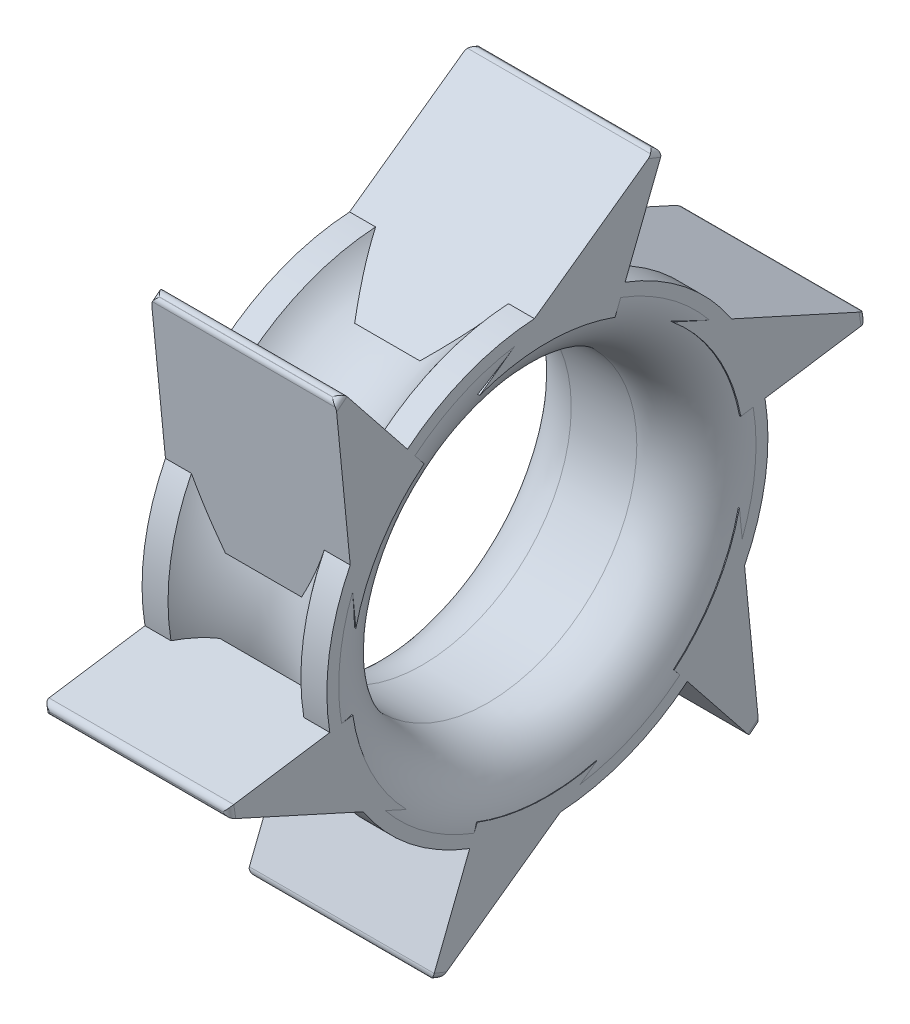
SolidWorks part; units mm, degrees
ref_plane "Front Plane" through (0, 0, 0) normal (0, 0, 1) x (1, 0, 0)
ref_plane "Top Plane" through (0, 0, 0) normal (0, 1, 0) x (1, 0, 0)
ref_plane "Right Plane" through (0, 0, 0) normal (1, 0, 0) x (0, 0, -1)
sketch "Sketch1" plane through (0, 0, 0) normal (0, 0, 1) x (1, 0, 0)
  line L0 (11.1435, 37) -> (15.5, 37)
  line L1 (-15.5, 37) -> (-11.1435, 37)
  line L2 (-15.5, 37) -> (-15.5, 25)
  line L3 (-15.5, 25) -> (15.5, 25)
  line L4 (15.5, 37) -> (15.5, 25)
  line L5 (-15.5, 37) -> (15.5, 25) construction
  line L6 (-15.5, 25) -> (15.5, 37) construction
  line L7 (0, 0) -> (-44.1868, 0) construction
  line L8 (-44.1868, 0) -> (70.9544, 0) construction
  arc A0 (-11.1435, 37) -> (11.1435, 37) centre (0, 45) ccw
  point P0 (0, 31)
  point P8 (0, 25)
  dimension "D4" = 8
  dimension "D1" = 25
  dimension "D2" = 37
  dimension "D3" = 31
revolve "Revolve1" add sketch "Sketch1" angle 360 about L8
fillet "Fillet1" radius 10 2 edges at (-15.5, 0, 25) (15.5, 0, 25)
sketch "Sketch2" plane through (0, 0, 0) normal (1, 0, 0) x (0, 0, -1)
  line L0 (0, -0.6164) -> (0, 55.3462) construction
  line L1 (-56.5594, 59.2727) -> (-53.6248, 59.2727)
  line L2 (19.3584, 50.7239) -> (11.3584, 30.3672)
  line L3 (0, -0.6164) -> (33.4372, 45.5458) construction
  line L4 (-11.3584, 30.3672) -> (17.8913, 51.298)
  line L5 (17.8913, 51.298) -> (19.3584, 50.7239)
  line L6 (20.6196, 25.0203) -> (53.371, 10.1547)
  line L7 (53.6074, 8.5971) -> (31.978, 5.3469)
  line L8 (53.371, 10.1547) -> (53.6074, 8.5971)
  line L9 (31.978, -5.3469) -> (35.4798, -41.1433)
  line L10 (34.249, -42.1268) -> (20.6196, -25.0203)
  line L11 (35.4798, -41.1433) -> (34.249, -42.1268)
  line L12 (11.3584, -30.3672) -> (-17.8913, -51.298)
  line L13 (-19.3584, -50.7239) -> (-11.3584, -30.3672)
  line L14 (-17.8913, -51.298) -> (-19.3584, -50.7239)
  line L15 (-20.6196, -25.0203) -> (-53.371, -10.1547)
  line L16 (-53.6074, -8.5971) -> (-31.978, -5.3469)
  line L17 (-53.371, -10.1547) -> (-53.6074, -8.5971)
  line L18 (-31.978, 5.3469) -> (-35.4798, 41.1433)
  line L19 (-34.249, 42.1268) -> (-20.6196, 25.0203)
  line L20 (-35.4798, 41.1433) -> (-34.249, 42.1268)
  circle A0 centre (0, -0.6164) radius 33
  circle A2 centre (0, -0.6164) radius 57 construction
  arc A4 (-15.0607, 28.7464) -> (19.3584, 26.1091) centre (0, -0.6164) cw
  circle A6 centre (0, -0.6164) radius 33
  circle A8 centre (0, -0.6164) radius 33
  circle A10 centre (0, -0.6164) radius 33
  circle A12 centre (0, -0.6164) radius 33
  circle A14 centre (0, -0.6164) radius 33
  circle A16 centre (0, -0.6164) radius 33
  circle A18 centre (0, -0.6164) radius 33
  circle A20 centre (0, -0.6164) radius 33
  circle A22 centre (0, -0.6164) radius 33
  circle A24 centre (0, -0.6164) radius 33
  point P26 (0, 0)
  point P57 (0, -0.6164)
  point P59 (0, 0)
  dimension "D2" = 11
  dimension "D1" = 24
  dimension "D4" = 6
sketch "Sketch3" plane through (-15.5, 0, 0) normal (-1, 0, 0) x (0, 0, 1)
extrude "Boss-Extrude1" add sketch "Sketch2" along normal mid plane 31 contours A0 L19 L20 L18 | A0 L2 L5 L4 | A0 L7 L8 L6 | A0 L10 L11 L9 | A0 L13 L14 L12 | A0 L16 L17 L15
fillet "Fillet9" radius 1 24 edges at (0, -50.7239, 19.3584) (-15.5, -51.011, 18.6248) (15.5, -51.011, 18.6248) (0, -51.298, 17.8913) (0, 42.1268, 34.249) (-15.5, 41.635, 34.8644) (15.5, 41.635, 34.8644) (0, 41.1433, 35.4798) (0, -8.5971, 53.6074) (-15.5, -9.3759, 53.4892) (15.5, -9.3759, 53.4892) (0, -10.1547, 53.371) (0, -42.1268, -34.249) (-15.5, -41.635, -34.8644) (15.5, -41.635, -34.8644) (0, -41.1433, -35.4798) (0, 50.7239, -19.3584) (-15.5, 51.011, -18.6248) (15.5, 51.011, -18.6248) (0, 51.298, -17.8913) (0, 8.5971, -53.6074) (-15.5, 9.3759, -53.4892) (15.5, 9.3759, -53.4892) (0, 10.1547, -53.371)
